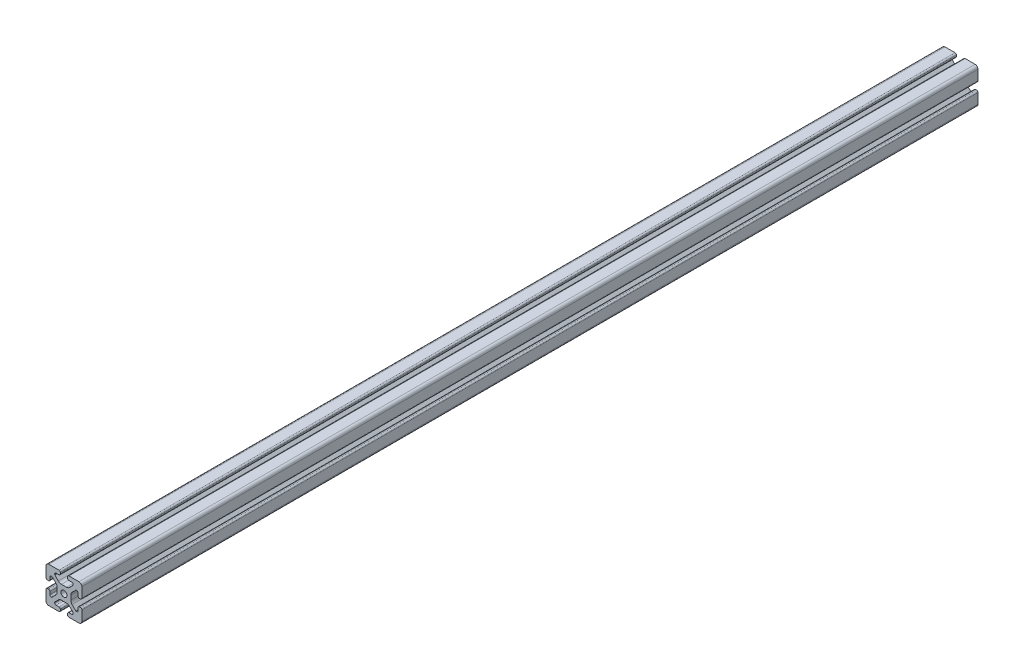
SolidWorks part; units mm, degrees
ref_plane "Front Plane" through (0, 0, 0) normal (0, 0, 1) x (1, 0, 0)
ref_plane "Top Plane" through (0, 0, 0) normal (0, 1, 0) x (1, 0, 0)
ref_plane "Right Plane" through (0, 0, 0) normal (1, 0, 0) x (0, 0, -1)
sketch "Sketch1" plane through (0, 0, 0) normal (0, 0, 1) x (1, 0, 0)
  line L0 (0, 19.7407) -> (0, -19.7407) construction
  line L1 (19.0335, 0) -> (-20.7246, 0) construction
  line L2 (-8.715, -15.5246) -> (-5.63, -15.5246)
  line L3 (-10.285, -13.9546) -> (-10.285, -13.4925)
  line L4 (-6.2171, -9.1098) -> (-10.0624, -12.9551)
  line L5 (2.7773, -7.685) -> (-2.7773, -7.685)
  line L6 (10.0624, -12.9551) -> (6.2171, -9.1098)
  line L7 (10.285, -13.9546) -> (10.285, -13.4925)
  line L8 (5.63, -15.5246) -> (8.715, -15.5246)
  line L9 (4.06, -18.43) -> (4.06, -17.0946)
  line L10 (-4.06, -18.43) -> (-4.06, -17.0946)
  line L11 (15.68, -8.7154) -> (15.68, -5.63)
  line L12 (-14.11, -10.2854) -> (-13.8169, -10.2854)
  line L13 (20, -16.83) -> (20, -5.63)
  line L14 (20, 5.63) -> (20, 13.0011)
  line L15 (-16.83, 20) -> (-5.63, 20)
  line L16 (5.63, 20) -> (12.9796, 20)
  line L17 (-8.715, 15.5246) -> (-5.63, 15.5246)
  line L18 (-20, -17.0184) -> (-20, -5.7579)
  line L19 (-20, 5.573) -> (-20, 13.0045)
  line L20 (-15.68, -8.7154) -> (-15.68, -5.7579)
  line L21 (-16.6746, -20) -> (-5.63, -20)
  line L22 (5.63, -20) -> (13, -20)
  line L23 (14.11, -10.2854) -> (13.6201, -10.2854)
  line L24 (13.1637, -9.947) -> (9.0762, -5.8595)
  line L25 (7.685, -2.5008) -> (7.685, 2.5008)
  line L26 (9.0762, 5.8595) -> (13.2795, 10.0628)
  line L27 (13.8169, 10.2854) -> (14.11, 10.2854)
  line L28 (15.68, 8.7154) -> (15.68, 5.63)
  line L29 (17.25, 4.06) -> (18.43, 4.06)
  line L30 (20, 13.0011) -> (20, 16.83)
  line L31 (16.83, 20) -> (12.9796, 20)
  line L32 (4.06, 18.43) -> (4.06, 17.0946)
  line L33 (5.63, 15.5246) -> (8.715, 15.5246)
  line L34 (10.285, 13.9546) -> (10.285, 13.4925)
  line L35 (10.0624, 12.9551) -> (6.2171, 9.1098)
  line L36 (2.7773, 7.685) -> (-2.7773, 7.685)
  line L37 (-6.2171, 9.1098) -> (-10.0624, 12.9551)
  line L38 (-10.285, 13.4925) -> (-10.285, 13.9546)
  line L39 (-4.06, 17.0946) -> (-4.06, 18.43)
  line L40 (-20, 16.83) -> (-20, 13.0045)
  line L41 (-18.43, 4.003) -> (-17.25, 4.003)
  line L42 (-15.68, 5.573) -> (-15.68, 8.4757)
  line L43 (-14.0552, 10.0447) -> (-13.7199, 10.033)
  line L44 (-13.0405, 9.8238) -> (-9.0762, 5.8595)
  line L45 (-7.685, 2.5008) -> (-7.685, -2.5008)
  line L46 (-9.0762, -5.8595) -> (-13.2795, -10.0628)
  line L47 (-17.2485, -4.1204) -> (-18.43, -4.1204)
  line L48 (13, -20) -> (16.83, -20)
  line L49 (18.43, -4.06) -> (17.25, -4.06)
  arc A0 (-5.63, -15.5246) -> (-4.06, -17.0946) centre (-5.63, -17.0946) cw
  arc A1 (-8.715, -15.5246) -> (-10.285, -13.9546) centre (-8.715, -13.9546) cw
  arc A2 (-10.285, -13.4925) -> (-10.0624, -12.9551) centre (-9.525, -13.4925) cw
  arc A3 (-6.2171, -9.1098) -> (-2.7773, -7.685) centre (-2.7773, -12.5496) cw
  arc A4 (2.7773, -7.685) -> (6.2171, -9.1098) centre (2.7773, -12.5496) cw
  arc A5 (10.0624, -12.9551) -> (10.285, -13.4925) centre (9.525, -13.4925) cw
  arc A6 (10.285, -13.9546) -> (8.715, -15.5246) centre (8.715, -13.9546) cw
  arc A7 (4.06, -17.0946) -> (5.63, -15.5246) centre (5.63, -17.0946) cw
  arc A8 (5.63, -20) -> (4.06, -18.43) centre (5.63, -18.43) cw
  arc A9 (-4.06, -18.43) -> (-5.63, -20) centre (-5.63, -18.43) cw
  circle A10 centre (0, 0) radius 3.4
  arc A11 (17.25, -4.06) -> (15.68, -5.63) centre (17.25, -5.63) ccw
  arc A12 (14.11, -10.2854) -> (15.68, -8.7154) centre (14.11, -8.7154) ccw
  arc A13 (13.1637, -9.947) -> (13.6201, -10.2854) centre (13.8117, -9.55) ccw
  arc A14 (7.685, -2.5008) -> (9.0762, -5.8595) centre (12.435, -2.5008) ccw
  arc A15 (9.0762, 5.8595) -> (7.685, 2.5008) centre (12.435, 2.5008) ccw
  arc A16 (13.8169, 10.2854) -> (13.2795, 10.0628) centre (13.8169, 9.5254) ccw
  arc A17 (15.68, 8.7154) -> (14.11, 10.2854) centre (14.11, 8.7154) ccw
  arc A18 (15.68, 5.63) -> (17.25, 4.06) centre (17.25, 5.63) ccw
  arc A19 (18.43, 4.06) -> (20, 5.63) centre (18.43, 5.63) ccw
  arc A20 (20, 16.83) -> (16.83, 20) centre (16.83, 16.83) ccw
  arc A21 (5.63, 20) -> (4.06, 18.43) centre (5.63, 18.43) ccw
  arc A22 (4.06, 17.0946) -> (5.63, 15.5246) centre (5.63, 17.0946) ccw
  arc A23 (10.285, 13.9546) -> (8.715, 15.5246) centre (8.715, 13.9546) ccw
  arc A24 (10.0624, 12.9551) -> (10.285, 13.4925) centre (9.525, 13.4925) ccw
  arc A25 (2.7773, 7.685) -> (6.2171, 9.1098) centre (2.7773, 12.5496) ccw
  arc A26 (-6.2171, 9.1098) -> (-2.7773, 7.685) centre (-2.7773, 12.5496) ccw
  arc A27 (-10.285, 13.4925) -> (-10.0624, 12.9551) centre (-9.525, 13.4925) ccw
  arc A28 (-8.715, 15.5246) -> (-10.285, 13.9546) centre (-8.715, 13.9546) ccw
  arc A29 (-5.63, 15.5246) -> (-4.06, 17.0946) centre (-5.63, 17.0946) ccw
  arc A30 (-4.06, 18.43) -> (-5.63, 20) centre (-5.63, 18.43) ccw
  arc A31 (-16.83, 20) -> (-20, 16.83) centre (-16.83, 16.83) ccw
  arc A32 (-20, 5.573) -> (-18.43, 4.003) centre (-18.43, 5.573) ccw
  arc A33 (-17.25, 4.003) -> (-15.68, 5.573) centre (-17.25, 5.573) ccw
  arc A34 (-14.0552, 10.0447) -> (-15.68, 8.4757) centre (-14.11, 8.4757) ccw
  arc A35 (-13.0405, 9.8238) -> (-13.7199, 10.033) centre (-13.5779, 9.2864) ccw
  arc A36 (-7.685, 2.5008) -> (-9.0762, 5.8595) centre (-12.435, 2.5008) ccw
  arc A37 (-9.0762, -5.8595) -> (-7.685, -2.5008) centre (-12.435, -2.5008) ccw
  arc A38 (-13.8169, -10.2854) -> (-13.2795, -10.0628) centre (-13.8169, -9.5254) ccw
  arc A39 (-15.68, -8.7154) -> (-14.11, -10.2854) centre (-14.11, -8.7154) ccw
  arc A40 (-15.68, -5.7579) -> (-17.2485, -4.1204) centre (-17.2485, -5.6904) ccw
  arc A41 (-18.43, -4.1204) -> (-20, -5.7579) centre (-18.4315, -5.6904) ccw
  arc A42 (-20, -17.0184) -> (-16.6746, -20) centre (-16.8354, -16.8341) ccw
  arc A43 (16.83, -20) -> (20, -16.83) centre (16.83, -16.83) ccw
  arc A44 (20, -5.63) -> (18.43, -4.06) centre (18.43, -5.63) ccw
  dimension "D1" = 6.8
  dimension "D2" = 4.32
  dimension "D3" = 15.37
  dimension "D4" = 20.57
  dimension "D5" = 15.37
  dimension "D6" = 40
  dimension "D7" = 20
  dimension "D8" = 4.32
  dimension "D9" = 8.12
extrude "Boss-Extrude2" add sketch "Sketch1" along normal blind 1000
